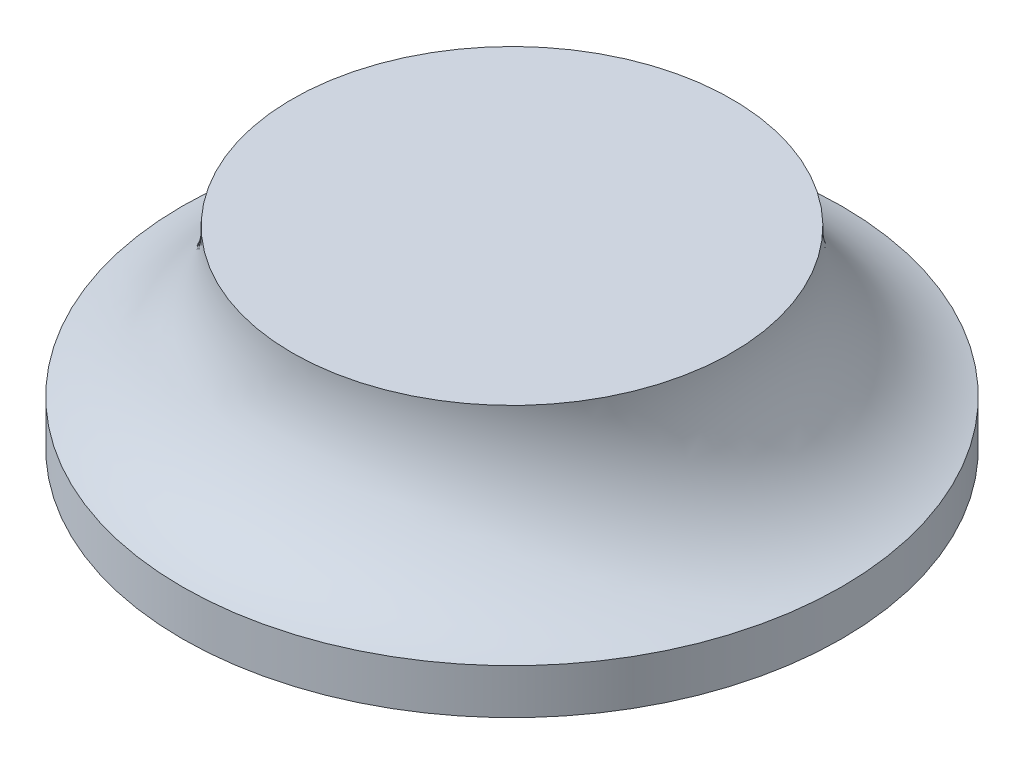
SolidWorks part; units mm, degrees
ref_plane "Front Plane" through (0, 0, 0) normal (0, 0, 1) x (1, 0, 0)
ref_plane "Top Plane" through (0, 0, 0) normal (0, 1, 0) x (1, 0, 0)
ref_plane "Right Plane" through (0, 0, 0) normal (1, 0, 0) x (0, 0, -1)
sketch "Sketch1" plane through (0, 0, 0) normal (0, 0, 1) x (1, 0, 0)
  line L0 (-0.15, 0.0877) -> (-0.15, -0.0877)
  line L1 (-0.15, -0.0877) -> (0.15, -0.0877)
  line L3 (-0.15, 0.0877) -> (0.05, 0.0877)
  line L4 (0.15, -0.0877) -> (0.15, -0.0467)
  line L5 (-0.1324, -0.0598) -> (0.1843, 0.0832) construction
  line L6 (-0.15, 0.0877) -> (0.15, -0.0877) construction
  arc A0 (0.05, 0.0877) -> (0.15, -0.0467) centre (0.1843, 0.0832) ccw
  point P0 (0, 0)
  dimension "D1" = 0.3
  dimension "D2" = 0.041
  dimension "D3" = 0.1753
  dimension "D4" = 0.2
revolve "Revolve1" add sketch "Sketch1" angle 360 about L0
